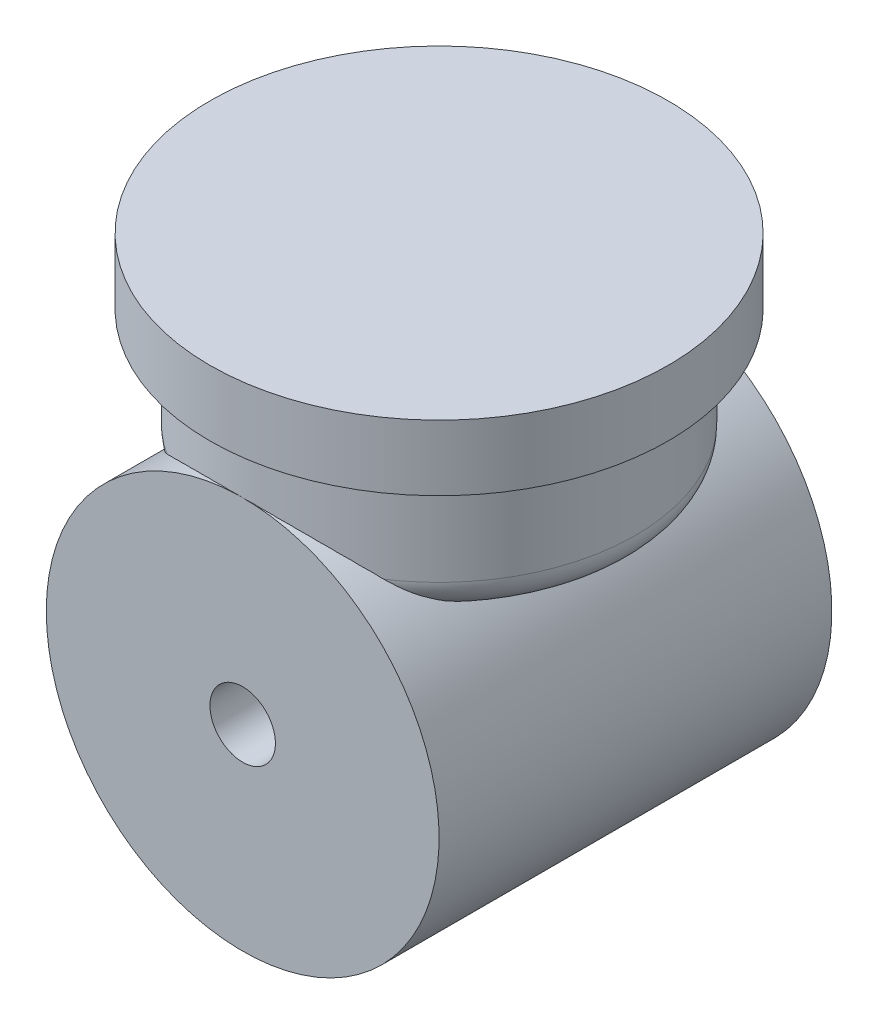
SolidWorks part; units mm, degrees
material "Acciaio al carbonio semplice"
ref_plane "Front Plane" through (0, 0, 0) normal (0, 0, 1) x (1, 0, 0)
ref_plane "Top Plane" through (0, 0, 0) normal (0, 1, 0) x (1, 0, 0)
ref_plane "Right Plane" through (0, 0, 0) normal (1, 0, 0) x (0, 0, -1)
other "Centro di massa"
sketch "Sketch1" plane through (0, 0, 0) normal (0, 1, 0) x (1, 0, 0)
  circle A0 centre (0, 0) radius 30
  dimension "D1" = 60
extrude "Boss-Extrude1" add sketch "Sketch1" along normal blind 20
sketch "Sketch2" plane through (0, 20, 0) normal (0, 1, 0) x (1, 0, 0)
  circle A2 centre (0, 0) radius 35
  circle A3 centre (0, 0) radius 35
  dimension "D1" = 5
extrude "Boss-Extrude2" add sketch "Sketch2" along normal blind 10
sketch "Sketch3" plane through (0, 0, 0) normal (0, 0, -1) x (-1, 0, 0)
  circle A0 centre (0, -20) radius 30
  dimension "D1" = 60
  dimension "D2" = 20
extrude "Boss-Extrude3" add sketch "Sketch3" along normal mid plane 60 separate body
sketch "Sketch4" plane through (0, 0, -30) normal (0, 0, -1) x (-1, 0, 0)
  circle A0 centre (0, -20) radius 5
  circle A2 centre (0, -20) radius 30 construction
  dimension "D1" = 10
extrude "Cut-Extrude1" cut sketch "Sketch4" against normal through all
fillet "Raccordo1" radius 5 1 edges at (0, 0, 30)
